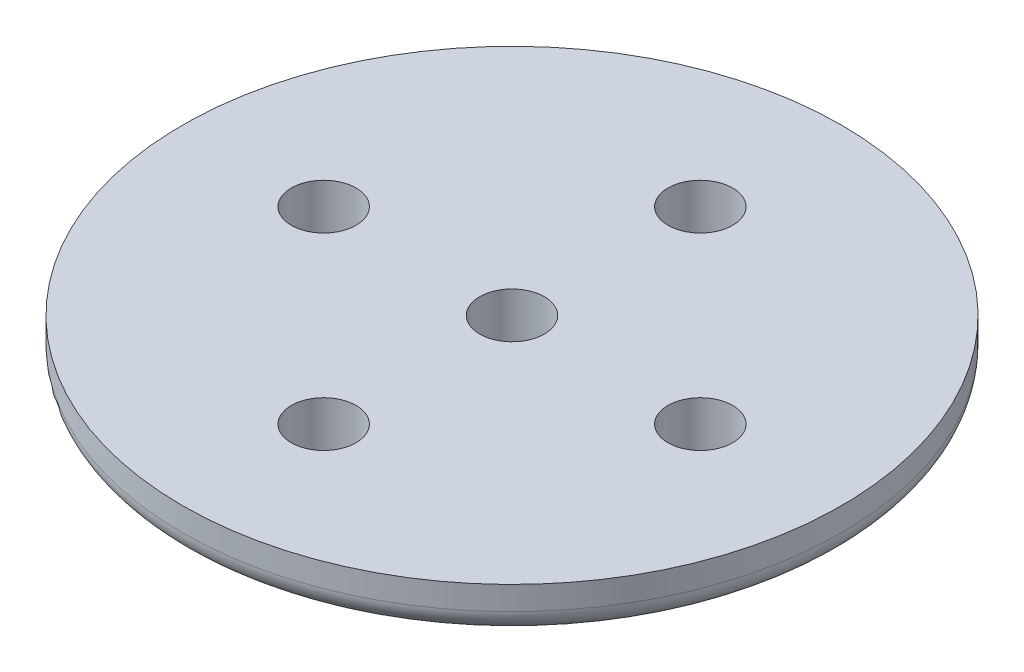
SolidWorks part; units mm, degrees
ref_plane "Front Plane" through (0, 0, 0) normal (0, 0, 1) x (1, 0, 0)
ref_plane "Top Plane" through (0, 0, 0) normal (0, 1, 0) x (1, 0, 0)
ref_plane "Right Plane" through (0, 0, 0) normal (1, 0, 0) x (0, 0, -1)
sketch "Sketch1" plane through (0, 0, 0) normal (0, 0, 1) x (1, 0, 0)
  line L1 (0, 0) -> (20.6375, 0)
  line L2 (0, 0) -> (0, 3.175)
  line L3 (0, 3.175) -> (22.225, 3.175)
  line L4 (22.225, 1.5875) -> (22.225, 3.175)
  arc A0 (20.6375, 0) -> (22.225, 1.5875) centre (20.6375, 1.5875) ccw
  dimension "D3" = 1.5875
  dimension "D1" = 22.225
  dimension "D2" = 3.175
revolve "Revolve1" add sketch "Sketch1" angle 360 about L2
sketch "Sketch2" plane through (0, 3.175, 0) normal (0, 1, 0) x (1, 0, 0)
  circle A0 centre (0, 0) radius 2.1828
  circle A1 centre (12.7, 0) radius 2.1828
  circle A2 centre (-12.7, 0) radius 2.1828
  circle A3 centre (0, 12.7) radius 2.1828
  circle A4 centre (0, -12.7) radius 2.1828
  dimension "D1" = 4.3656
  dimension "D2" = 4.3656
  dimension "D3" = 4.3656
  dimension "D4" = 4.3656
  dimension "D5" = 4.3656
  dimension "D6" = 12.7
  dimension "D7" = 12.7
  dimension "D8" = 12.7
  dimension "D9" = 12.7
extrude "Cut-Extrude1" cut sketch "Sketch2" against normal through all both and the other way through all
